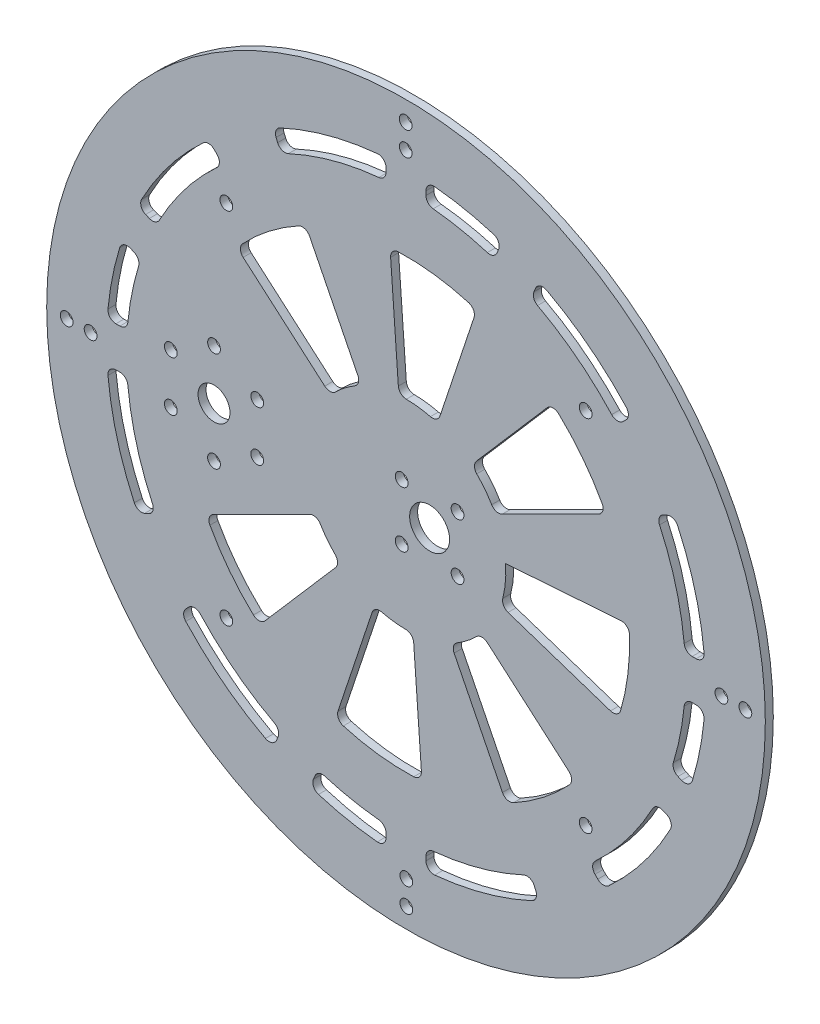
SolidWorks part; units mm, degrees
ref_plane "Front Plane" through (0, 0, 0) normal (0, 0, 1) x (1, 0, 0)
ref_plane "Top Plane" through (0, 0, 0) normal (0, 1, 0) x (1, 0, 0)
ref_plane "Right Plane" through (0, 0, 0) normal (1, 0, 0) x (0, 0, -1)
sketch "Sketch1" plane through (0, 0, 0) normal (0, 0, 1) x (1, 0, 0)
  line L0 (59.5611, 32.5317) -> (58.6365, 32.1487)
  line L1 (2.5892, 25.5487) -> (11.1252, 51.203)
  line L2 (48.4913, 47.3319) -> (49.199, 48.0397)
  line L3 (-7.835, 26.857) -> (-9.7662, 53.8251)
  line L4 (66.7519, 5) -> (65.7472, 5)
  line L5 (65.7472, -5) -> (66.7519, -5)
  line L6 (63.1341, -23.1878) -> (62.2059, -22.8033)
  line L7 (58.3791, -32.0421) -> (59.3073, -32.4266)
  line L9 (41.4203, -54.403) -> (42.128, -55.1107)
  line L10 (26.62, -65.4728) -> (26.237, -64.5481)
  line L12 (-0.9117, -72.6636) -> (-0.9117, -71.6589)
  line L13 (-10.9117, -71.6589) -> (-10.9117, -72.6636)
  line L14 (-29.0994, -69.0458) -> (-28.715, -68.1176)
  line L15 (-37.9538, -64.2908) -> (-38.3382, -65.219)
  line L16 (18.165, 12.0546) -> (42.3412, 24.1591)
  line L17 (-60.3147, -47.3319) -> (-61.0224, -48.0397)
  line L18 (-71.3845, -32.5317) -> (-70.4598, -32.1487)
  line L19 (11.7192, 20.3508) -> (29.4229, 40.7856)
  line L20 (-78.5753, -5) -> (-77.5706, -5)
  line L21 (-77.5706, 5) -> (-78.5753, 5)
  line L22 (-74.9575, 23.1878) -> (-74.0293, 22.8033)
  line L23 (-70.2025, 32.0421) -> (-71.1307, 32.4266)
  line L25 (-53.2436, 54.403) -> (-53.9513, 55.1107)
  line L26 (-38.4434, 65.4728) -> (-38.0604, 64.5481)
  line L28 (-10.9117, 72.6636) -> (-10.9117, 71.6589)
  line L29 (-0.9117, 71.6589) -> (-0.9117, 72.6636)
  line L30 (17.2761, 69.0458) -> (16.8916, 68.1176)
  line L31 (26.1304, 64.2908) -> (26.5149, 65.219)
  line L32 (60.5081, 22.1) -> (65.1385, 24.018) [skipped]
  line L33 (-72.3315, -22.1) -> (-76.9619, -24.018) [skipped]
  line L34 (-28.0117, 66.4198) -> (-29.9297, 71.0502) [skipped]
  line L35 (16.1883, -66.4198) -> (18.1063, -71.0502) [skipped]
  line L36 (19.637, -8.5009) -> (45.2913, -17.0369)
  line L37 (19.0245, 1.7857) -> (47.9134, 3.8545)
  line L40 (6.1429, -24.0767) -> (18.2474, -48.2529)
  line L41 (14.4391, -17.6308) -> (34.874, -35.3346)
  line L44 (-14.4126, -25.5487) -> (-22.9486, -51.203)
  line L45 (-3.9884, -26.857) -> (-2.0572, -53.8251)
  line L48 (-29.9884, -12.0546) -> (-54.1646, -24.1591)
  line L49 (-23.5425, -20.3508) -> (-41.2463, -40.7856)
  line L56 (-17.9663, 24.0767) -> (-30.0708, 48.2529)
  line L57 (-26.2624, 17.6308) -> (-46.6973, 35.3346)
  line L60 (17.8097, -7.8929) -> (47.2241, -17.68) [skipped]
  line L61 (19.0245, 1.7857) -> (49.9453, 4) [skipped]
  line L62 (16.4429, 11.1924) -> (44.1627, 25.0711) [skipped]
  line L63 (10.4581, 18.8952) -> (30.7567, 42.3253) [skipped]
  line L64 (1.9812, 23.7214) -> (11.7683, 53.1358) [skipped]
  line L65 (-7.6974, 24.9361) -> (-9.9117, 55.857) [skipped]
  line L66 (-17.1041, 22.3546) -> (-30.9827, 50.0744) [skipped]
  line L67 (-24.8069, 16.3698) -> (-48.237, 36.6684) [skipped]
  line L68 (-29.633, 7.8929) -> (-59.0475, 17.68) [skipped]
  line L69 (-30.8478, -1.7857) -> (-61.7686, -4) [skipped]
  line L70 (-28.2663, -11.1924) -> (-55.9861, -25.0711) [skipped]
  line L71 (-22.2815, -18.8952) -> (-42.5801, -42.3253) [skipped]
  line L72 (-13.8046, -23.7214) -> (-23.5917, -53.1358) [skipped]
  line L73 (-4.126, -24.9361) -> (-1.9117, -55.857) [skipped]
  line L74 (5.2807, -22.3546) -> (19.1594, -50.0744) [skipped]
  line L75 (12.9835, -16.3698) -> (36.4136, -36.6684) [skipped]
  line L76 (-31.4604, 8.5009) -> (-57.1147, 17.0369) [skipped]
  line L77 (-32.7687, -1.9233) -> (-59.7368, -3.8545) [skipped]
  circle A0 centre (-5.9117, 0) radius 90
  arc A1 (-61.0793, -50.8088) -> (-41.125, -66.2195) centre (-5.9117, 0) ccw
  arc A2 (-57.4286, -47.3921) -> (-38.8601, -61.7608) centre (-5.9117, 0) ccw
  arc A3 (-26.2851, -66.9696) -> (-12.7172, -69.6684) centre (-5.9117, 0) ccw
  circle A4 centre (-5.9117, 0) radius 70 construction
  circle A5 centre (-5.9117, 0) radius 75 construction
  arc A6 (-27.8363, -71.7238) -> (-13.1035, -74.6544) centre (-5.9117, 0) ccw
  arc A7 (16.013, 71.7238) -> (1.2801, 74.6544) centre (-5.9117, 0) ccw
  arc A8 (14.4617, 66.9696) -> (0.8939, 69.6684) centre (-5.9117, 0) ccw
  arc A9 (49.256, 50.8088) -> (29.3016, 66.2195) centre (-5.9117, 0) ccw
  arc A10 (45.6052, 47.3921) -> (27.0368, 61.7608) centre (-5.9117, 0) ccw
  arc A11 (-56.7205, 55.1676) -> (-72.1312, 35.2133) centre (-5.9117, 0) ccw
  arc A12 (-53.3038, 51.5169) -> (-67.6725, 32.9485) centre (-5.9117, 0) ccw
  arc A13 (-77.6355, 21.9247) -> (-80.5661, 7.1918) centre (-5.9117, 0) ccw
  arc A14 (-72.8813, 20.3734) -> (-75.5801, 6.8056) centre (-5.9117, 0) ccw
  arc A15 (41.4804, -51.5169) -> (55.8491, -32.9485) centre (-5.9117, 0) ccw
  arc A16 (44.8971, -55.1676) -> (60.3078, -35.2133) centre (-5.9117, 0) ccw
  arc A17 (61.0579, -20.3734) -> (63.7567, -6.8056) centre (-5.9117, 0) ccw
  arc A18 (65.8122, -21.9247) -> (68.7427, -7.1918) centre (-5.9117, 0) ccw
  arc A19 (68.7427, 7.1918) -> (62.1412, 31.5246) centre (-5.9117, 0) ccw
  arc A20 (63.7567, 6.8056) -> (57.5876, 29.4592) centre (-5.9117, 0) ccw
  arc A21 (-75.5801, -6.8056) -> (-69.4109, -29.4592) centre (-5.9117, 0) ccw
  arc A22 (-80.5661, -7.1918) -> (-73.9646, -31.5246) centre (-5.9117, 0) ccw
  arc A23 (-12.7172, 69.6684) -> (-35.3709, 63.4992) centre (-5.9117, 0) ccw
  arc A24 (-13.1035, 74.6544) -> (-37.4363, 68.0529) centre (-5.9117, 0) ccw
  arc A25 (1.2801, -74.6544) -> (25.6129, -68.0529) centre (-5.9117, 0) ccw
  arc A26 (0.8939, -69.6684) -> (23.5475, -63.4992) centre (-5.9117, 0) ccw
  arc A27 (0.2024, 24.2408) -> (-5.8454, 24.9999) centre (-5.9117, 0) ccw
  arc A28 (9.7882, 53.7542) -> (-7.8402, 55.9668) centre (-5.9117, 0) ccw
  arc A29 (-30.0708, 48.2529) -> (-32.8201, 49.1115) centre (-31.8591, 47.3575) ccw
  arc A30 (-26.2624, 17.6308) -> (-23.5424, 17.7245) centre (-24.9529, 19.1425) ccw
  arc A31 (15.5525, 12.8176) -> (11.8128, 17.6307) centre (-5.9117, 0) ccw
  arc A32 (43.1998, 26.9085) -> (32.2992, 40.9381) centre (-5.9117, 0) ccw
  arc A33 (-17.9663, 24.0767) -> (-18.7293, 21.4641) centre (-19.7547, 23.1813) cw
  arc A34 (-46.6973, 35.3346) -> (-46.8498, 38.2109) centre (-45.3877, 36.8462) cw
  arc A35 (18.3292, -6.114) -> (19.0245, 1.7857) centre (-5.9117, 0) ccw
  arc A36 (47.8425, -15.6999) -> (50.0551, 1.9285) centre (-5.9117, 0) ccw
  arc A39 (6.9059, -21.4641) -> (11.719, -17.7245) centre (-5.9117, 0) ccw
  arc A40 (20.9968, -49.1115) -> (35.0264, -38.2109) centre (-5.9117, 0) ccw
  arc A43 (-12.0257, -24.2408) -> (-5.978, -24.9999) centre (-5.9117, 0) ccw
  arc A44 (-21.6116, -53.7542) -> (-3.9832, -55.9668) centre (-5.9117, 0) ccw
  arc A45 (-54.1646, -24.1591) -> (-55.0231, -26.9085) centre (-53.2692, -25.9474) ccw
  arc A46 (-23.5425, -20.3508) -> (-23.6362, -17.6307) centre (-25.0541, -19.0412) ccw
  arc A47 (-27.3758, -12.8176) -> (-23.6362, -17.6307) centre (-5.9117, 0) ccw
  arc A48 (-55.0231, -26.9085) -> (-44.1225, -40.9381) centre (-5.9117, 0) ccw
  arc A49 (-29.9884, -12.0546) -> (-27.3758, -12.8176) centre (-29.093, -13.843) cw
  arc A50 (-41.2463, -40.7856) -> (-44.1225, -40.9381) centre (-42.7579, -39.4761) cw
  arc A53 (-22.9486, -51.203) -> (-21.6116, -53.7542) centre (-21.0509, -51.8344) ccw
  arc A54 (-3.9884, -26.857) -> (-5.978, -24.9999) centre (-5.9833, -26.9999) ccw
  arc A55 (-18.7293, 21.4641) -> (-23.5424, 17.7245) centre (-5.9117, 0) ccw
  arc A56 (-32.8201, 49.1115) -> (-46.8498, 38.2109) centre (-5.9117, 0) ccw
  arc A57 (-14.4126, -25.5487) -> (-12.0257, -24.2408) centre (-12.5149, -26.1801) cw
  arc A58 (-2.0572, -53.8251) -> (-3.9832, -55.9668) centre (-4.0521, -53.968) cw
  arc A59 (-9.9117, 55.857) -> (-30.9827, 50.0744) centre (-5.9117, 0) ccw [skipped]
  arc A60 (-7.6974, 24.9361) -> (-17.1041, 22.3546) centre (-5.9117, 0) ccw [skipped]
  arc A61 (-24.8069, 16.3698) -> (-29.633, 7.8929) centre (-5.9117, 0) ccw [skipped]
  arc A62 (-48.237, 36.6684) -> (-59.0475, 17.68) centre (-5.9117, 0) ccw [skipped]
  arc A63 (-61.7686, -4) -> (-55.9861, -25.0711) centre (-5.9117, 0) ccw [skipped]
  arc A64 (-30.8478, -1.7857) -> (-28.2663, -11.1924) centre (-5.9117, 0) ccw [skipped]
  arc A65 (-42.5801, -42.3253) -> (-23.5917, -53.1358) centre (-5.9117, 0) ccw [skipped]
  arc A66 (-22.2815, -18.8952) -> (-13.8046, -23.7214) centre (-5.9117, 0) ccw [skipped]
  arc A67 (-4.126, -24.9361) -> (5.2807, -22.3546) centre (-5.9117, 0) ccw [skipped]
  arc A68 (-1.9117, -55.857) -> (19.1594, -50.0744) centre (-5.9117, 0) ccw [skipped]
  arc A69 (12.9835, -16.3698) -> (17.8097, -7.8929) centre (-5.9117, 0) ccw [skipped]
  arc A70 (36.4136, -36.6684) -> (47.2241, -17.68) centre (-5.9117, 0) ccw [skipped]
  arc A71 (49.9453, 4) -> (44.1627, 25.0711) centre (-5.9117, 0) ccw [skipped]
  arc A72 (19.0245, 1.7857) -> (16.4429, 11.1924) centre (-5.9117, 0) ccw [skipped]
  arc A73 (10.4581, 18.8952) -> (1.9812, 23.7214) centre (-5.9117, 0) ccw [skipped]
  arc A74 (30.7567, 42.3253) -> (11.7683, 53.1358) centre (-5.9117, 0) ccw [skipped]
  arc A75 (18.2474, -48.2529) -> (20.9968, -49.1115) centre (20.0358, -47.3575) ccw
  arc A76 (14.4391, -17.6308) -> (11.719, -17.7245) centre (13.1295, -19.1425) ccw
  arc A77 (6.1429, -24.0767) -> (6.9059, -21.4641) centre (7.9313, -23.1813) cw
  arc A78 (34.874, -35.3346) -> (35.0264, -38.2109) centre (33.5644, -36.8462) cw
  arc A79 (45.2913, -17.0369) -> (47.8425, -15.6999) centre (45.9227, -15.1392) ccw
  arc A80 (26.5149, 65.219) -> (29.3016, 66.2195) centre (28.3626, 64.4536) cw
  arc A81 (17.2761, 69.0458) -> (16.013, 71.7238) centre (15.4283, 69.8112) ccw
  arc A82 (26.1304, 64.2908) -> (27.0368, 61.7608) centre (27.9781, 63.5254) ccw
  arc A83 (16.8916, 68.1176) -> (14.4617, 66.9696) centre (15.0438, 68.883) cw
  arc A84 (-0.9117, 72.6636) -> (1.2801, 74.6544) centre (1.0883, 72.6636) cw
  arc A85 (-10.9117, 72.6636) -> (-13.1035, 74.6544) centre (-12.9117, 72.6636) ccw
  arc A86 (-0.9117, 71.6589) -> (0.8939, 69.6684) centre (1.0883, 71.6589) ccw
  arc A87 (-10.9117, 71.6589) -> (-12.7172, 69.6684) centre (-12.9117, 71.6589) cw
  arc A88 (19.637, -8.5009) -> (18.3292, -6.114) centre (20.2684, -6.6032) cw
  arc A89 (-38.4434, 65.4728) -> (-37.4363, 68.0529) centre (-36.5956, 66.2382) cw
  arc A90 (47.9134, 3.8545) -> (50.0551, 1.9285) centre (48.0563, 1.8596) cw
  arc A91 (-38.0604, 64.5481) -> (-35.3709, 63.4992) centre (-36.2126, 65.3135) ccw
  arc A92 (-53.9513, 55.1107) -> (-56.7205, 55.1676) centre (-55.3656, 53.6965) ccw
  arc A93 (-53.2436, 54.403) -> (-53.3038, 51.5169) centre (-54.6578, 52.9888) cw
  arc A94 (-71.1307, 32.4266) -> (-72.1312, 35.2133) centre (-70.3653, 34.2743) cw
  arc A95 (-74.9575, 23.1878) -> (-77.6355, 21.9247) centre (-75.7229, 21.34) ccw
  arc A96 (-70.2025, 32.0421) -> (-67.6725, 32.9485) centre (-69.4371, 33.8898) ccw
  arc A97 (-74.0293, 22.8033) -> (-72.8813, 20.3734) centre (-74.7947, 20.9555) cw
  arc A98 (-78.5753, 5) -> (-80.5661, 7.1918) centre (-78.5753, 7) cw
  arc A99 (-78.5753, -5) -> (-80.5661, -7.1918) centre (-78.5753, -7) ccw
  arc A100 (-77.5706, 5) -> (-75.5801, 6.8056) centre (-77.5706, 7) ccw
  arc A101 (-77.5706, -5) -> (-75.5801, -6.8056) centre (-77.5706, -7) cw
  arc A102 (-71.3845, -32.5317) -> (-73.9646, -31.5246) centre (-72.1499, -30.6839) cw
  arc A103 (-70.4598, -32.1487) -> (-69.4109, -29.4592) centre (-71.2252, -30.3009) ccw
  arc A104 (-61.0224, -48.0397) -> (-61.0793, -50.8088) centre (-59.6082, -49.4539) ccw
  arc A105 (42.3412, 24.1591) -> (43.1998, 26.9085) centre (41.4458, 25.9474) ccw
  arc A106 (-60.3147, -47.3319) -> (-57.4286, -47.3921) centre (-58.9005, -48.7462) cw
  arc A107 (11.7192, 20.3508) -> (11.8128, 17.6307) centre (13.2308, 19.0412) ccw
  arc A108 (-38.3382, -65.219) -> (-41.125, -66.2195) centre (-40.186, -64.4536) cw
  arc A109 (-29.0994, -69.0458) -> (-27.8363, -71.7238) centre (-27.2517, -69.8112) ccw
  arc A110 (-37.9538, -64.2908) -> (-38.8601, -61.7608) centre (-39.8015, -63.5254) ccw
  arc A111 (-28.715, -68.1176) -> (-26.2851, -66.9696) centre (-26.8672, -68.883) cw
  arc A112 (-10.9117, -72.6636) -> (-13.1035, -74.6544) centre (-12.9117, -72.6636) cw
  arc A113 (-0.9117, -72.6636) -> (1.2801, -74.6544) centre (1.0883, -72.6636) ccw
  arc A114 (-10.9117, -71.6589) -> (-12.7172, -69.6684) centre (-12.9117, -71.6589) ccw
  arc A115 (-0.9117, -71.6589) -> (0.8939, -69.6684) centre (1.0883, -71.6589) cw
  arc A116 (18.165, 12.0546) -> (15.5525, 12.8176) centre (17.2696, 13.843) cw
  arc A117 (26.62, -65.4728) -> (25.6129, -68.0529) centre (24.7722, -66.2382) cw
  arc A118 (29.4229, 40.7856) -> (32.2992, 40.9381) centre (30.9345, 39.4761) cw
  arc A119 (26.237, -64.5481) -> (23.5475, -63.4992) centre (24.3892, -65.3135) ccw
  arc A120 (42.128, -55.1107) -> (44.8971, -55.1676) centre (43.5422, -53.6965) ccw
  arc A121 (41.4203, -54.403) -> (41.4804, -51.5169) centre (42.8345, -52.9888) cw
  arc A122 (59.3073, -32.4266) -> (60.3078, -35.2133) centre (58.5419, -34.2743) cw
  arc A123 (63.1341, -23.1878) -> (65.8122, -21.9247) centre (63.8995, -21.34) ccw
  arc A124 (58.3791, -32.0421) -> (55.8491, -32.9485) centre (57.6137, -33.8898) ccw
  arc A125 (62.2059, -22.8033) -> (61.0579, -20.3734) centre (62.9713, -20.9555) cw
  arc A126 (66.7519, -5) -> (68.7427, -7.1918) centre (66.7519, -7) cw
  arc A127 (66.7519, 5) -> (68.7427, 7.1918) centre (66.7519, 7) ccw
  arc A128 (65.7472, -5) -> (63.7567, -6.8056) centre (65.7472, -7) ccw
  arc A129 (65.7472, 5) -> (63.7567, 6.8056) centre (65.7472, 7) cw
  arc A130 (59.5611, 32.5317) -> (62.1412, 31.5246) centre (60.3265, 30.6839) cw
  arc A131 (49.199, 48.0397) -> (49.256, 50.8088) centre (47.7848, 49.4539) ccw
  arc A132 (48.4913, 47.3319) -> (45.6052, 47.3921) centre (47.0771, 48.7462) cw
  arc A133 (58.6365, 32.1487) -> (57.5876, 29.4592) centre (59.4018, 30.3009) ccw
  arc A134 (11.1252, 51.203) -> (9.7882, 53.7542) centre (9.2275, 51.8344) ccw
  arc A135 (-7.835, 26.857) -> (-5.8454, 24.9999) centre (-5.8401, 26.9999) ccw
  arc A136 (2.5892, 25.5487) -> (0.2024, 24.2408) centre (0.6915, 26.1801) cw
  arc A137 (-9.7662, 53.8251) -> (-7.8402, 55.9668) centre (-7.7713, 53.968) cw
  arc A138 (-59.6659, 15.6999) -> (-61.8785, -1.9285) centre (-5.9117, 0) ccw [skipped]
  arc A139 (-30.1525, 6.114) -> (-30.9116, 0.0663) centre (-5.9117, 0) ccw [skipped]
  point P3 (69.0883, 0)
  point P5 (64.0883, 0)
  point P9 (-5.9117, 0)
  point P77 (-5.9117, 0)
  point P132 (-5.9117, 0)
  point P309 (50.5389, 49.3795)
  point P312 (46.9949, 45.8355)
  dimension "D1" = 15
  dimension "D4" = 16
  dimension "D5" = 2
  dimension "D2" = 5
  dimension "D3" = 16
extrude "Boss-Extrude1" add sketch "Sketch1" along normal blind 2
sketch "Sketch7" plane through (0, 0, 0) normal (0, 0, -1) x (-1, 0, 0)
  circle A0 centre (54, 0) radius 4
  circle A1 centre (54, -12.5) radius 1.6
  circle A2 centre (43.1747, -6.25) radius 1.6
  circle A3 centre (43.1747, 6.25) radius 1.6
  circle A4 centre (54, 12.5) radius 1.6
  circle A5 centre (64.8253, 6.25) radius 1.6
  circle A6 centre (64.8253, -6.25) radius 1.6
  circle A7 centre (0, 0) radius 5
  circle A8 centre (-7, 7) radius 1.6
  circle A9 centre (7, 7) radius 1.6
  circle A10 centre (7, -7) radius 1.6
  circle A11 centre (-7, -7) radius 1.6
  point P18 (54, 0)
  dimension "D1" = 6
extrude "Cut-Extrude4" cut sketch "Sketch7" against normal blind 2
sketch "Sketch8" plane through (0, 0, 2) normal (0, 0, 1) x (1, 0, 0)
  circle A0 centre (-50.9117, 45) radius 1.6
  circle A1 centre (39.0883, 45) radius 1.6
  circle A2 centre (39.0883, -45) radius 1.6
  circle A3 centre (-50.9117, -45) radius 1.6
extrude "Cut-Extrude5" cut sketch "Sketch8" against normal blind 2
sketch "Sketch9" plane through (0, 0, 0) normal (0, 0, -1) x (-1, 0, 0)
  circle A0 centre (5.8305, -85) radius 1.6
  circle A1 centre (5.8305, -79) radius 1.6
  circle A2 centre (-79.0883, 0.0811) radius 1.6
  circle A3 centre (-73.0883, 0.0811) radius 1.6
  circle A4 centre (5.9928, 85) radius 1.6
  circle A5 centre (5.9928, 79) radius 1.6
  circle A6 centre (90.9117, -0.0811) radius 1.6
  circle A7 centre (84.9117, -0.0811) radius 1.6
  point P9 (5.9117, 0)
  point P23 (5.9117, 0)
  dimension "D1" = 4
extrude "Cut-Extrude6" cut sketch "Sketch9" against normal blind 2
sketch "Sketch3" plane through (0, 0, 0) normal (0, 0, -1) x (-1, 0, 0)
  line L0 (54, 0) -> (54, 12.5) construction
  circle A0 centre (-7, 7) radius 1.5
  circle A1 centre (7, 7) radius 1.5
  circle A2 centre (7, -7) radius 1.5
  circle A3 centre (-7, -7) radius 1.5
  circle A4 centre (54, 0) radius 3
  circle A5 centre (54, 12.5) radius 1.6
  circle A6 centre (64.8253, 6.25) radius 1.6
  circle A7 centre (64.8253, -6.25) radius 1.6
  circle A8 centre (54, -12.5) radius 1.6
  circle A9 centre (43.1747, -6.25) radius 1.6
  circle A10 centre (43.1747, 6.25) radius 1.6
  point P12 (0, 0)
  point P27 (54, 0)
  dimension "D1" = 4
  dimension "D2" = 6
extrude "Cut-Extrude2" cut sketch "Sketch3" against normal blind 2
sketch "Sketch4" plane through (0, 0, 53.08) normal (0, 0, 1) x (1, 0, 0)
  point P4 (-5.9117, 0)
sketch "Sketch5" plane through (0, 0, 2) normal (0, 0, 1) x (1, 0, 0)
  circle A0 centre (-50.9117, 45) radius 1.6
  circle A1 centre (39.0883, 45) radius 1.6
  circle A2 centre (39.0883, -45) radius 1.6
  circle A3 centre (-50.9117, -45) radius 1.6
extrude "Cut-Extrude3" cut sketch "Sketch5" against normal blind 2
